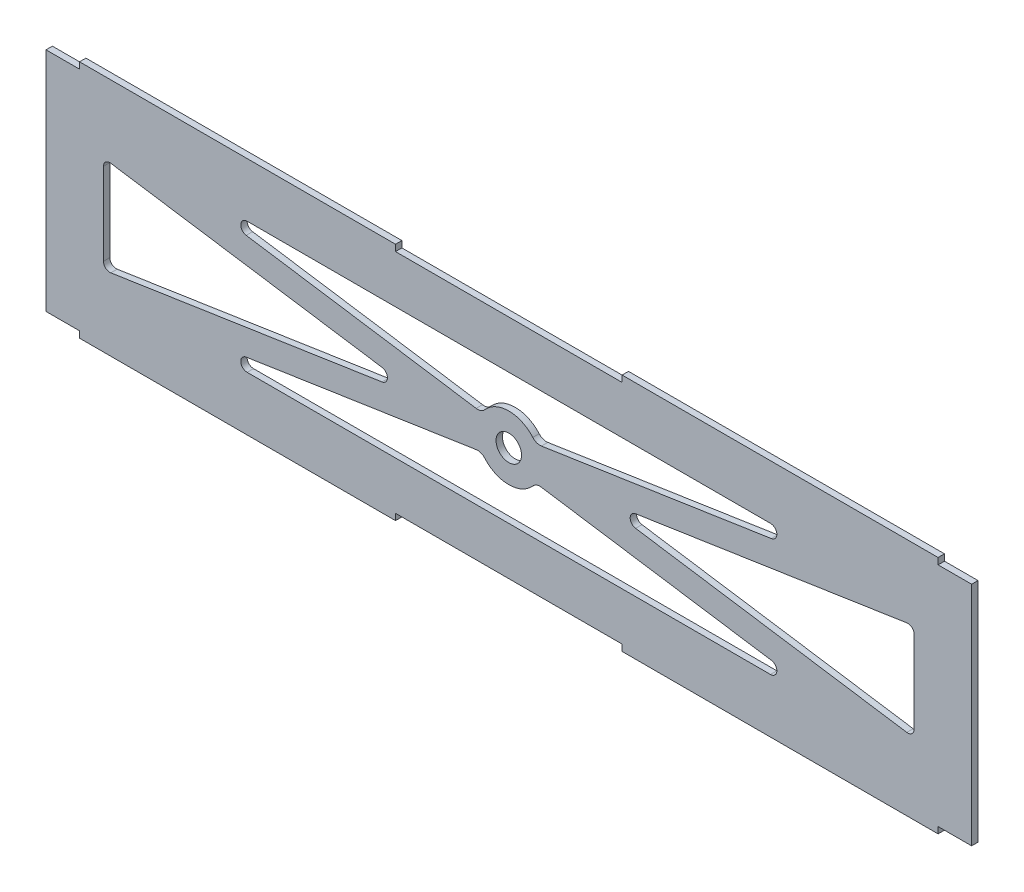
SolidWorks part; units mm, degrees
ref_plane "前视基准面" through (0, 0, 0) normal (0, 0, 1) x (1, 0, 0)
ref_plane "上视基准面" through (0, 0, 0) normal (0, 1, 0) x (1, 0, 0)
ref_plane "右视基准面" through (0, 0, 0) normal (1, 0, 0) x (0, 0, -1)
sketch "草图1" plane through (0, 0, 0) normal (0, 0, 1) x (1, 0, 0)
  line L1 (-145, -35.5) -> (145, -35.5)
  line L2 (-145, -35.5) -> (-145, 35.5)
  line L3 (-145, 35.5) -> (145, 35.5)
  line L4 (145, -35.5) -> (145, 35.5)
  line L5 (-145, -35.5) -> (145, 35.5) construction
  line L6 (-145, 35.5) -> (145, -35.5) construction
  point P0 (0, 0)
  dimension "D1" = 290
  dimension "D2" = 71
extrude "凸台-拉伸1" add sketch "草图1" along normal blind 2
sketch "草图2" plane through (0, 0, 2) normal (0, 0, 1) x (1, 0, 0)
  line L0 (145, 35.5) -> (-145, 35.5) construction
  line L1 (-134.5, 33.5) -> (-35.5, 33.5)
  line L2 (-134.5, 33.5) -> (-134.5, 37.5)
  line L3 (-134.5, 37.5) -> (-35.5, 37.5)
  line L4 (-35.5, 33.5) -> (-35.5, 37.5)
  line L5 (-134.5, 33.5) -> (-35.5, 37.5) construction
  line L6 (-134.5, 37.5) -> (-35.5, 33.5) construction
  point P0 (-85, 35.5)
  dimension "D1" = 99
  dimension "D2" = 2
  dimension "D3" = 85
extrude "凸台-拉伸2" add sketch "草图2" against normal blind 2
mirror "镜向1" about plane through (0, 0, 0) normal (1, 0, 0) of "凸台-拉伸2"
mirror "镜向2" about plane through (0, 0, 0) normal (0, 1, 0) of "镜向1", "凸台-拉伸2"
sketch "草图3" plane through (0, 0, 2) normal (0, 0, 1) x (1, 0, 0)
  line L0 (35.5, 35.5) -> (-35.5, 35.5) construction
  line L1 (-122, -20.5) -> (122, -20.5)
  line L2 (-127, -15.5) -> (-127, 15.5)
  line L3 (-122, 20.5) -> (122, 20.5)
  line L4 (127, -15.5) -> (127, 15.5)
  line L5 (-127, -20.5) -> (127, 20.5) construction
  line L6 (-127, 20.5) -> (127, -20.5) construction
  line L7 (145, -35.5) -> (145, 35.5) construction
  arc A0 (122, -20.5) -> (127, -15.5) centre (122, -15.5) ccw
  arc A1 (-127, 15.5) -> (-122, 20.5) centre (-122, 15.5) cw
  arc A2 (-122, -20.5) -> (-127, -15.5) centre (-122, -15.5) cw
  arc A3 (122, 20.5) -> (127, 15.5) centre (122, 15.5) cw
  point P0 (0, 0)
  dimension "D3" = 5
  dimension "D1" = 15
  dimension "D2" = 18
extrude "切除-拉伸1" cut sketch "草图3" against normal blind 2
sketch "草图4" plane through (0, 0, 2) normal (0, 0, 1) x (1, 0, 0)
  line L0 (-125.5355, 19.0355) -> (-9.887, 1.4992) construction
  line L1 (125.5355, 19.0355) -> (9.887, 1.4992) construction
  line L2 (-130.0488, 15.6742) -> (-26.6807, 0)
  line L3 (124.9359, 22.9903) -> (8.4619, 5.3288)
  line L4 (-124.9359, 22.9903) -> (-8.4619, 5.3288)
  line L5 (132.9046, 16.1072) -> (26.6807, 0)
  line L6 (124.9359, 22.9903) -> (-126.1352, -15.0807) construction
  line L7 (-126.1352, 15.0807) -> (124.9359, -22.9903) construction
  line L8 (-124.9359, 22.9903) -> (126.1352, -15.0807) construction
  line L9 (126.1352, 15.0807) -> (-124.9359, -22.9903) construction
  line L10 (132.9046, 16.1072) -> (124.9359, 22.9903)
  line L11 (132.9703, -16.1172) -> (124.9359, -22.9903)
  line L12 (-130.0488, 15.6742) -> (-124.9359, 22.9903)
  line L13 (-130.1388, -15.6878) -> (-124.9359, -22.9903)
  line L14 (-8.4619, -5.3288) -> (-124.9359, -22.9903)
  line L15 (8.4619, -5.3288) -> (124.9359, -22.9903)
  line L16 (-9.887, -1.4992) -> (-125.5355, -19.0355) construction
  line L17 (125.5355, 19.0355) -> (-125.5355, -19.0355) construction
  line L18 (9.887, -1.4992) -> (125.5355, -19.0355) construction
  line L19 (-125.5355, 19.0355) -> (125.5355, -19.0355) construction
  line L22 (-26.6807, 0) -> (-130.1388, -15.6878)
  line L23 (26.6807, 0) -> (132.9703, -16.1172)
  arc A0 (-122, 20.5) -> (-127, 15.5) centre (-122, 15.5) ccw construction
  arc A1 (122, -20.5) -> (127, -15.5) centre (122, -15.5) ccw construction
  arc A2 (127, 15.5) -> (122, 20.5) centre (122, 15.5) ccw construction
  arc A3 (-127, -15.5) -> (-122, -20.5) centre (-122, -15.5) ccw construction
  circle A4 centre (0, 0) radius 10
  line M4 (127, 15.5) -> (127, -15.5)
  arc M5 (127, -15.5) -> (122, -20.5) centre (122, -15.5) cw
  line M6 (122, -20.5) -> (-122, -20.5)
  arc M7 (-122, -20.5) -> (-127, -15.5) centre (-122, -15.5) cw
  line M8 (-127, -15.5) -> (-127, 15.5)
  arc M9 (-127, 15.5) -> (-122, 20.5) centre (-122, 15.5) cw
  line M10 (-122, 20.5) -> (122, 20.5)
  arc M11 (122, 20.5) -> (127, 15.5) centre (122, 15.5) cw
  line M12 (-145, -35.5) -> (-134.5, -35.5)
  line M13 (-134.5, -35.5) -> (-134.5, -37.5)
  line M14 (-134.5, -37.5) -> (-35.5, -37.5)
  line M15 (-35.5, -37.5) -> (-35.5, -35.5)
  line M16 (-35.5, -35.5) -> (35.5, -35.5)
  line M17 (35.5, -35.5) -> (35.5, -37.5)
  line M18 (35.5, -37.5) -> (134.5, -37.5)
  line M19 (134.5, -37.5) -> (134.5, -35.5)
  line M20 (134.5, -35.5) -> (145, -35.5)
  line M21 (145, -35.5) -> (145, 35.5)
  line M22 (145, 35.5) -> (134.5, 35.5)
  line M23 (134.5, 35.5) -> (134.5, 37.5)
  line M24 (134.5, 37.5) -> (35.5, 37.5)
  line M25 (35.5, 37.5) -> (35.5, 35.5)
  line M26 (35.5, 35.5) -> (-35.5, 35.5)
  line M27 (-35.5, 35.5) -> (-35.5, 37.5)
  line M28 (-35.5, 37.5) -> (-134.5, 37.5)
  line M29 (-134.5, 37.5) -> (-134.5, 35.5)
  line M30 (-134.5, 35.5) -> (-145, 35.5)
  line M31 (-145, 35.5) -> (-145, -35.5)
  dimension "D3" = 20
  dimension "D1" = 4
  dimension "D2" = 4
extrude "凸台-拉伸3" add sketch "草图4" against normal up to surface (2 mm away) contours A4 L4 L2 L22 L14 M10 M9 M8 M7 M6 | A4 L15 L23 L5 L3 M6 M5 M4 M11 M10 | A4 | L23 L11 L15 L14 L13 L22 L2 L12 L4 L3 L10 L5 M31 M12 M13 M14 M15 M16 M17 M18 M19 M20 M21 M22 M23 M24 M25 M26 M27 M28 M29 M30 M4 M6 M8 M10 up to face at (0, 0, 0)
sketch "草图5" plane through (0, 0, 2) normal (0, 0, 1) x (1, 0, 0)
  circle A0 centre (0, 0) radius 4
  dimension "D1" = 8
extrude "切除-拉伸2" cut sketch "草图5" against normal blind 119
fillet "圆角1" radius 2 10 edges at (-26.6807, 0, 1) (26.6807, 0, 1) (127, 15.2119, 1) (127, -15.2119, 1) (108.5126, -20.5, 1) (-108.5126, -20.5, 1) (-127, -15.2119, 1) (-127, 15.2119, 1) (108.5126, 20.5, 1) (-108.5126, 20.5, 1)
fillet "圆角2" radius 3 4 edges at (-8.4619, -5.3288, 1) (8.4619, -5.3288, 1) (8.4619, 5.3288, 1) (-8.4619, 5.3288, 1)
